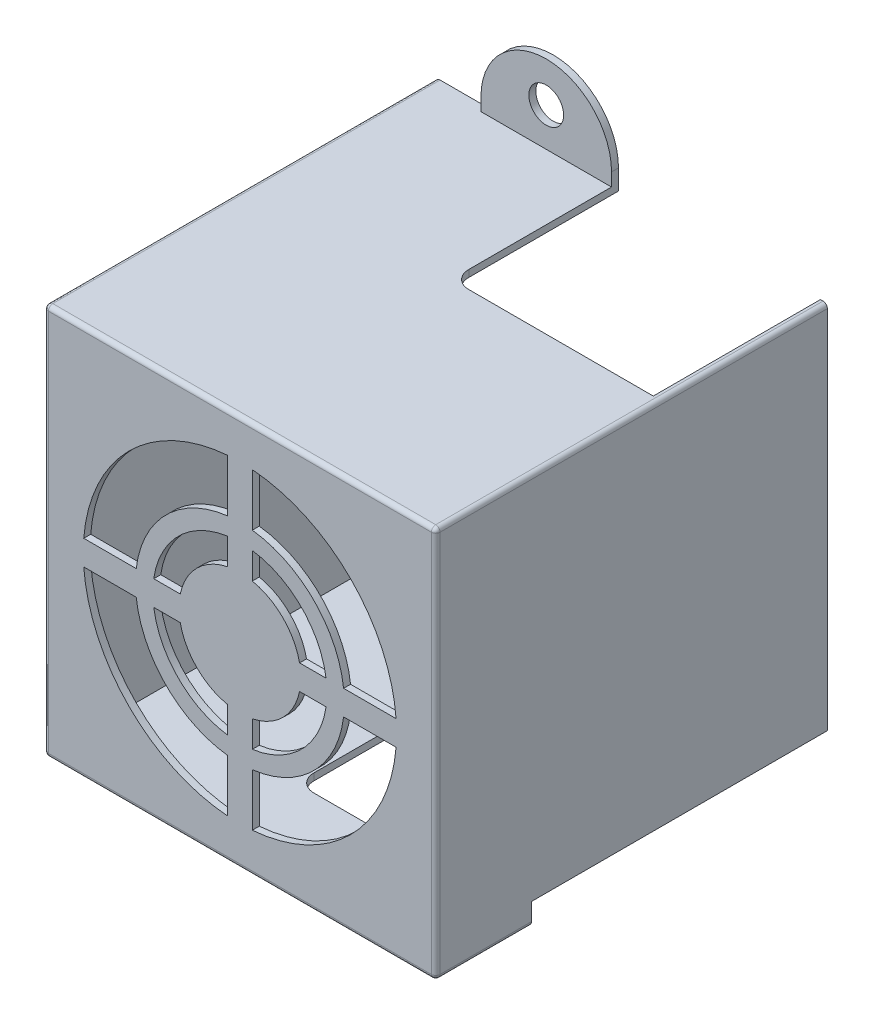
SolidWorks part; units mm, degrees
material "ABS"
ref_plane "Front Plane" through (0, 0, 0) normal (0, 0, 1) x (1, 0, 0)
ref_plane "Top Plane" through (0, 0, 0) normal (0, 1, 0) x (1, 0, 0)
ref_plane "Right Plane" through (0, 0, 0) normal (1, 0, 0) x (0, 0, -1)
sketch "Sketch1" plane through (0, 0, 0) normal (0, 1, 0) x (1, 0, 0)
  line L1 (0, 0) -> (45, 0)
  line L2 (0, 0) -> (0, -45)
  line L3 (0, -45) -> (45, -45)
  line L4 (45, 0) -> (45, -45)
  dimension "D1" = 45
  dimension "D2" = 45
extrude "Boss-Extrude1" add sketch "Sketch1" along normal blind 45
shell "Shell1" thickness 0.8
sketch "Sketch2" plane through (0, 0, 45) normal (0, 0, 1) x (1, 0, 0)
  line L0 (0, 45) -> (45, 0) construction
  line L1 (22.5, 40.5) -> (22.5, 4.5) construction
  line L2 (4.5, 22.5) -> (40.5, 22.5) construction
  line L4 (45, 45) -> (0, 45)
  line L5 (45, 45) -> (45, 0)
  line L6 (45, 0) -> (0, 0)
  line L7 (0, 45) -> (0, 0)
  line L8 (21.5, 39.5819) -> (23.5, 39.5819)
  line L9 (21.0767, 40.4436) -> (21.0767, 4.5564)
  line L11 (23.9233, 40.4436) -> (23.9233, 4.5564)
  line L12 (40.4436, 23.9233) -> (4.5564, 23.9233)
  line L14 (40.4436, 21.0767) -> (4.5564, 21.0767)
  line L15 (1.6075, 23.5) -> (1.6075, 21.5)
  circle A0 centre (22.5, 22.5) radius 12
  circle A1 centre (22.5, 22.5) radius 18
  circle A2 centre (22.5, 22.5) radius 10
  circle A3 centre (22.5, 22.5) radius 7
  point P25 (1.6075, 22.5)
  point P26 (22.5, 39.5819)
  dimension "D1" = 24
  dimension "D2" = 36
  dimension "D3" = 20
  dimension "D4" = 14
  dimension "D5" = 2
extrude "Cut-Extrude1" cut sketch "Sketch2" against normal blind 45 contours L9 A1 L12 A0 | L12 A1 L11 A0 | L11 A1 L14 A0 | L14 A1 L9 A0 | A3 L11 A2 L14 | A3 L12 A2 L11 | A3 L9 A2 L12 | A3 L14 A2 L9
sketch "Sketch3" plane through (45, 0, 0) normal (1, 0, 0) x (0, 0, -1)
  line L0 (-45, 0) -> (0, 0) construction
  line L1 (-34, 0) -> (0, 0)
  line L2 (-34, 0) -> (-34, 2.5)
  line L3 (-34, 2.5) -> (0, 2.5)
  line L4 (0, 0) -> (0, 2.5)
  line L5 (0, 45) -> (0, 0) construction
  dimension "D1" = 2.5
  dimension "D2" = 34
extrude "Cut-Extrude2" cut sketch "Sketch3" against normal blind 27
fillet "Fillet1" radius 2 1 edges at (18, 0.4, 34)
fillet "Fillet2" radius 0.5 2 edges at (0, 22.5, 45) (45, 22.5, 45)
fillet "Fillet3" radius 0.5 10 edges at (0, 0, 22.25) (0.1464, 0, 44.8536) (45, 0, 39.25) (44.8536, 0, 44.8536) (0, 45, 22.25) (0.1464, 45, 44.8536) (45, 45, 22.25) (44.8536, 45, 44.8536) (22.5, 0, 45) (22.5, 45, 45)
sketch "Sketch4" plane through (0, 0, 0) normal (0, 0, -1) x (-1, 0, 0)
  line L0 (-6, 45) -> (-6, 46.5)
  line L1 (-44.5, 45) -> (-0.5, 45) construction
  line L2 (-21, 45) -> (-21, 46.5)
  line L3 (0, 38) -> (1.5, 38)
  line L4 (0, 44.5) -> (0, 0.5) construction
  line L5 (0, 23) -> (1.5, 23)
  arc A0 (-6, 46.5) -> (-21, 46.5) centre (-13.5, 46.5) ccw
  arc A1 (1.5, 38) -> (1.5, 23) centre (1.5, 30.5) cw
  circle A2 centre (-13.5, 49.4) radius 2
  circle A3 centre (4.4, 30.5) radius 2
  point P19 (9, 30.5)
  point P21 (-13.5, 54)
  line M7 (0, 0.5) -> (0, 44.5)
  line M9 (-0.5, 45) -> (-44.5, 45)
  dimension "D2" = 7.5
  dimension "D6" = 7.5
  dimension "D7" = 2.9
  dimension "D8" = 2.9
  dimension "D10" = 4
  dimension "D11" = 4
  dimension "D1" = 1.5
  dimension "D3" = 5.5
  dimension "D4" = 1.5
  dimension "D5" = 1.5
  dimension "D9" = 6.5
extrude "Boss-Extrude2" add sketch "Sketch4" against normal blind 0.8 contours L0 A0 L2 A2 M9 | A1 L3 L5 A3 M7
sketch "Sketch5" plane through (0, 45, 0) normal (0, 1, 0) x (1, 0, 0)
  line L0 (21, 0) -> (21, -17.2)
  line L1 (23, -19.2) -> (44.2, -19.2)
  line L4 (21, 0) -> (44.2, 0)
  line L6 (44.2, 0) -> (44.2, -19.2)
  line L7 (44.5, -44.5) -> (44.5, 0) construction
  arc A0 (21, -17.2) -> (23, -19.2) centre (23, -17.2) ccw
  dimension "D2" = 2
  dimension "D1" = 17.2
  dimension "D3" = 0.3
extrude "Cut-Extrude4" cut sketch "Sketch5" against normal blind 0.8
